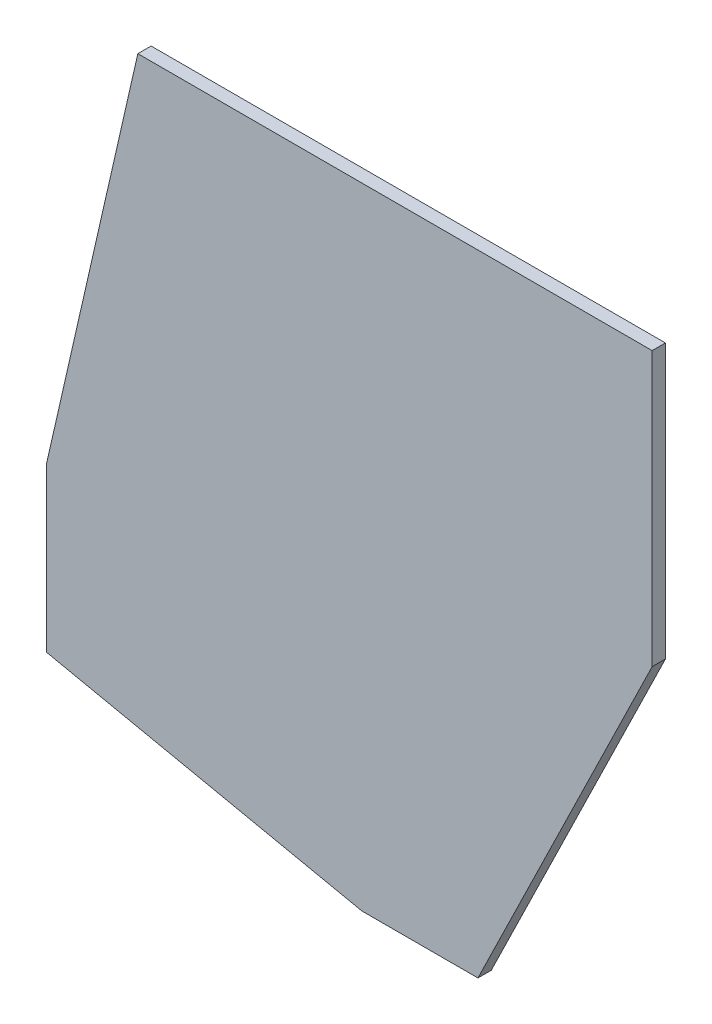
SolidWorks part; units mm, degrees
ref_plane "前视" through (0, 0, 0) normal (0, 0, 1) x (1, 0, 0)
ref_plane "上视" through (0, 0, 0) normal (0, 1, 0) x (1, 0, 0)
ref_plane "右视" through (0, 0, 0) normal (1, 0, 0) x (0, 0, -1)
sketch "草图1" plane through (0, 0, 0) normal (0, 0, 1) x (1, 0, 0)
  line L0 (730, -330) -> (520, -760)
  line L1 (110, 0) -> (730, 0)
  line L2 (0, -482.7866) -> (0, -680)
  line L3 (380, -760) -> (520, -760)
  line L4 (730, 0) -> (730, -330)
  line L5 (0, -482.7866) -> (110, 0)
  line L6 (0, 0) -> (0, 307.009) construction
  line L7 (0, 307.009) -> (0, -942.9561) construction
  line L8 (0, 0) -> (1145.1922, 0) construction
  line L9 (0, -680) -> (380, -760)
  line L10 (450, -1142.7556) -> (450, 165.6874) construction
  line L11 (510, 146.1947) -> (510, -423.4249) construction
  line L12 (-204.6726, -70) -> (986.8145, -70) construction
  line L13 (590, 146.1947) -> (590, -492.189) construction
  line L14 (-204.6726, -230) -> (918.5903, -230) construction
  line L15 (670, 146.1947) -> (670, -470.2598) construction
  line L16 (-204.6726, -150) -> (986.8145, -150) construction
  line L17 (150, 0) -> (150, -387.2631) construction
  line L18 (380, -470) -> (553.1035, -470) construction
  line L19 (250.9676, -370) -> (653.0032, -370) construction
  line L20 (380, -550) -> (553.1035, -550) construction
  line L21 (450, -400) -> (90.1534, -400) construction
  line L22 (380, -630) -> (553.1035, -630) construction
  line L23 (450, -150) -> (249.9573, -399.9658) construction
  line L24 (380, -710) -> (544.4186, -710) construction
  line L25 (249.9573, -399.9658) -> (0, -712.3029) construction
  line L26 (123.5646, -376.7449) -> (331.8306, -543.4161) construction
  line L27 (69.3486, -435.821) -> (277.7181, -602.575) construction
  line L29 (-53.2368, -650.7905) -> (192.5549, -343.6585) construction
  line L30 (506, -447.511) -> (506, -741.3026) construction
  line L31 (0, -482.7866) -> (213.7577, -653.8527) construction
  circle A0 centre (510, -70) radius 13
  circle A1 centre (590, -70) radius 13
  circle A2 centre (670, -70) radius 13
  circle A3 centre (510, -150) radius 13
  circle A4 centre (590, -150) radius 13
  circle A5 centre (670, -150) radius 13
  circle A6 centre (510, -230) radius 13
  circle A7 centre (590, -230) radius 13
  circle A8 centre (670, -230) radius 13
  circle A9 centre (230, -230) radius 13
  circle A10 centre (310, -230) radius 13
  circle A11 centre (390, -230) radius 13
  circle A12 centre (230, -150) radius 13
  circle A13 centre (310, -150) radius 13
  circle A14 centre (390, -150) radius 13
  circle A15 centre (230, -70) radius 13
  circle A16 centre (310, -70) radius 13
  circle A17 centre (390, -70) radius 13
  circle A18 centre (150, -70) radius 13
  circle A19 centre (150, -150) radius 13
  circle A20 centre (150, -230) radius 13
  circle A21 centre (590, -370) radius 13
  circle A22 centre (510, -370) radius 13
  circle A23 centre (390, -370) radius 13
  circle A24 centre (310, -370) radius 13
  circle A25 centre (506, -470) radius 13
  circle A26 centre (506, -550) radius 13
  circle A27 centre (506, -630) radius 13
  circle A28 centre (506, -710) radius 13
  circle A29 centre (394, -710) radius 13
  circle A30 centre (394, -630) radius 13
  circle A31 centre (394, -550) radius 13
  circle A32 centre (394, -470) radius 13
  circle A33 centre (149.4794, -397.4841) radius 13
  circle A34 centre (99.4931, -459.945) radius 13
  circle A35 centre (49.5068, -522.406) radius 13
  circle A36 centre (61.9815, -634.8532) radius 13
  circle A37 centre (111.9678, -572.3923) radius 13
  circle A38 centre (161.9541, -509.9313) radius 13
  circle A39 centre (211.9403, -447.4703) radius 13
  circle A40 centre (174.4287, -622.3785) radius 13
  circle A41 centre (224.415, -559.9176) radius 13
  circle A42 centre (274.4013, -497.4566) radius 13
  point P1 (110, 0)
  point P5 (520, -760)
  point P6 (730, -330)
  point P9 (249.9299, -400)
  point P16 (0, -680)
  point P17 (380, -760)
  point P110 (450, -150)
  point P111 (450, -400)
  point P122 (61.9815, -634.8532)
  dimension "D16" = 26
  dimension "D28" = 26
  dimension "D1" = 760
  dimension "D2" = 730
  dimension "D3" = 210
  dimension "D4" = 430
  dimension "D5" = 110
  dimension "D6" = 320.2
  dimension "D7" = 80
  dimension "D8" = 380
  dimension "D9" = 280
  dimension "D10" = 60
  dimension "D11" = 80
  dimension "D12" = 80
  dimension "D13" = 70
  dimension "D14" = 80
  dimension "D15" = 80
  dimension "D17" = 300
  dimension "D18" = 140
  dimension "D19" = 100
  dimension "D20" = 80
  dimension "D21" = 80
  dimension "D22" = 80
  dimension "D23" = 250
  dimension "D24" = 80
  dimension "D25" = 381
  dimension "D26" = 80
  dimension "D27" = 80
  dimension "D29" = 80
  dimension "D30" = 56
extrude "基体-拉伸" add sketch "草图1" along normal blind 16
sketch "草图2" plane through (0, 0, 16) normal (0, 0, 1) x (1, 0, 0)
  line L0 (110, 0) -> (730, 0)
  line L1 (730, 0) -> (730, -330)
  line L2 (730, -330) -> (520, -760)
  line L3 (520, -760) -> (380, -760)
  line L4 (380, -760) -> (0, -680)
  line L5 (0, -680) -> (0, -482.7866)
  line L6 (0, -482.7866) -> (110, 0)
extrude "凸台-拉伸1" add sketch "草图2" against normal blind 16
